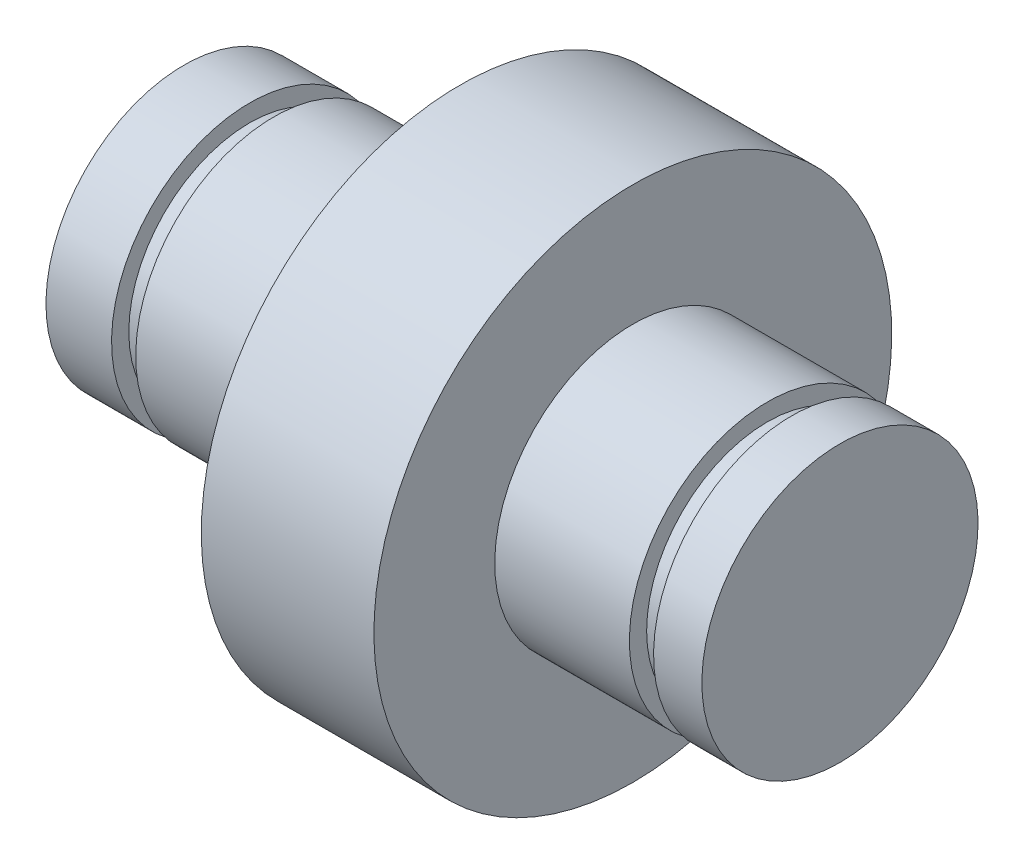
SolidWorks part; units mm, degrees
ref_plane "Piano frontale" through (0, 0, 0) normal (0, 0, 1) x (1, 0, 0)
ref_plane "Piano superiore" through (0, 0, 0) normal (0, 1, 0) x (1, 0, 0)
ref_plane "Piano destro" through (0, 0, 0) normal (1, 0, 0) x (0, 0, -1)
sketch "Schizzo1" plane through (0, 0, 0) normal (0, 0, 1) x (1, 0, 0)
  line L0 (-10.8005, 0) -> (11, 0) construction
  line L1 (-8, 0) -> (-8, 4)
  line L2 (-8, 4) -> (-6.1, 4)
  line L3 (-6.1, 4) -> (-6.1, 3.5)
  line L4 (-6.1, 3.5) -> (-5.4, 3.5)
  line L5 (-5.4, 3.5) -> (-5.4, 4)
  line L6 (-5.4, 4) -> (0, 4)
  line L7 (0, 4) -> (0, 7.5)
  line L8 (0, 7.5) -> (5, 7.5)
  line L9 (5, 7.5) -> (5, 4)
  line L10 (5, 4) -> (8.9, 4)
  line L11 (8.9, 4) -> (8.9, 3.5)
  line L12 (8.9, 3.5) -> (9.6, 3.5)
  line L13 (9.6, 3.5) -> (9.6, 4)
  line L14 (9.6, 4) -> (11, 4)
  line L15 (11, 4) -> (11, 0)
  line L16 (11, 0) -> (-8, 0)
  point P5 (8.875, 0)
  point P19 (4.4209, 3.9705)
  point P20 (0, 3.9705)
  point P21 (-6.5013, 0)
  point P22 (-10.8005, 0)
  point P23 (-7.1016, 0)
  point P24 (0, 0)
  point P25 (11, 0)
  point P26 (11, 0)
  point P27 (0, 0)
  point P28 (0, 0)
  dimension "D1" = 8
  dimension "D2" = 0.7
  dimension "D3" = 6.1
  dimension "D4" = 7
  dimension "D5" = 0.7
  dimension "D6" = 8
  dimension "D7" = 4.6
  dimension "D8" = 6
  dimension "D9" = 19
  dimension "D10" = 15
revolve "Rivoluzione1" add sketch "Schizzo1" angle 360 about L0
